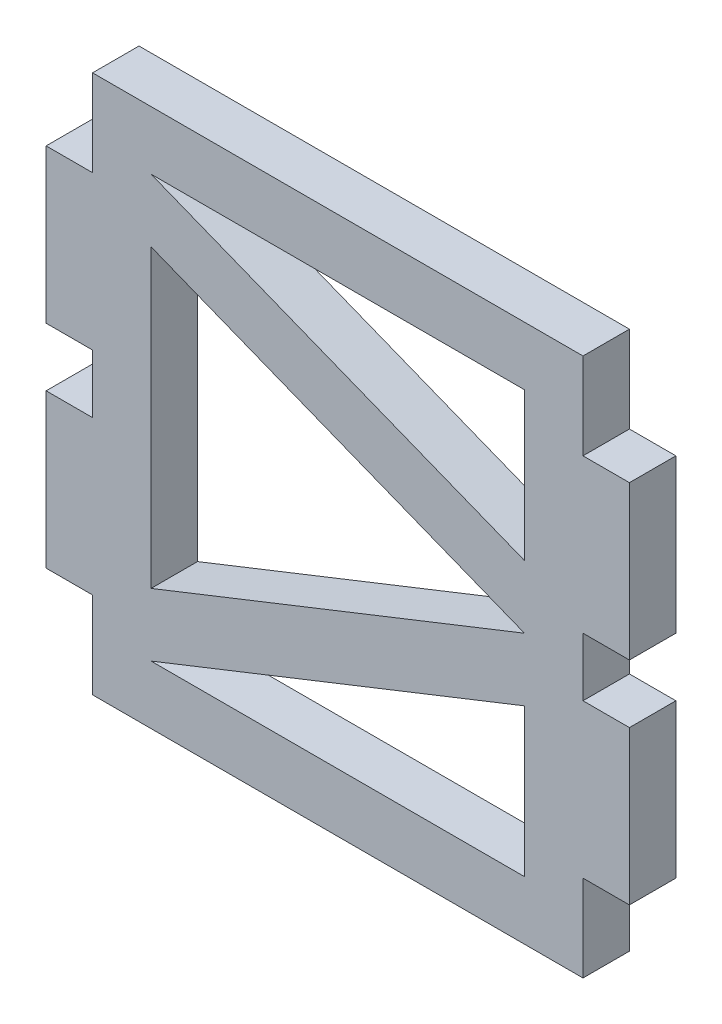
SolidWorks part; units mm, degrees
material "Mahogany"
ref_plane "Front Plane" through (0, 0, 0) normal (0, 0, 1) x (1, 0, 0)
ref_plane "Top Plane" through (0, 0, 0) normal (0, 1, 0) x (1, 0, 0)
ref_plane "Right Plane" through (0, 0, 0) normal (1, 0, 0) x (0, 0, -1)
sketch "Sketch1" plane through (0, 0, 0) normal (0, 0, 1) x (1, 0, 0)
  line L0 (3.175, 27.5) -> (0, 27.5) construction
  line L1 (0, 27.5) -> (0, 38) construction
  line L2 (3.175, 38) -> (0, 38) construction
  line L3 (3.175, 42) -> (0, 42) construction
  line L4 (0, 42) -> (0, 52.5) construction
  line L5 (3.175, 52.5) -> (0, 52.5) construction
  line L6 (36.7, 27.5) -> (39.875, 27.5) construction
  line L7 (39.875, 27.5) -> (39.875, 38) construction
  line L8 (36.7, 38) -> (39.875, 38) construction
  line L9 (36.7, 42) -> (39.875, 42) construction
  line L10 (39.875, 42) -> (39.875, 52.5) construction
  line L11 (36.7, 52.5) -> (39.875, 52.5) construction
  line L12 (3.175, 27.5) -> (0, 27.5)
  line L13 (0, 27.5) -> (0, 38)
  line L14 (3.175, 38) -> (0, 38)
  line L15 (3.175, 42) -> (0, 42)
  line L16 (0, 42) -> (0, 52.5)
  line L17 (3.175, 52.5) -> (0, 52.5)
  line L18 (36.7, 27.5) -> (39.875, 27.5)
  line L19 (39.875, 27.5) -> (39.875, 38)
  line L20 (36.7, 38) -> (39.875, 38)
  line L21 (36.7, 42) -> (39.875, 42)
  line L22 (39.875, 42) -> (39.875, 52.5)
  line L23 (36.7, 52.5) -> (39.875, 52.5)
  line L24 (39.875, 42) -> (39.875, 38) construction
  line L25 (0, 42) -> (0, 38) construction
  line L26 (0, 40) -> (39.875, 40) construction
  line L27 (36.7, 42) -> (36.7, 38)
  line L28 (3.175, 42) -> (3.175, 38)
  line L29 (36.7, 52.5) -> (36.7, 58.4125)
  line L30 (36.7, 58.4125) -> (3.175, 58.4125)
  line L31 (3.175, 58.4125) -> (3.175, 52.5)
  line L32 (36.7, 27.5) -> (36.7, 21.5875)
  line L33 (36.7, 21.5875) -> (3.175, 21.5875)
  line L34 (3.175, 21.5875) -> (3.175, 27.5)
  line L35 (32.7, 40) -> (7.175, 50.1102)
  line L36 (7.175, 50.1102) -> (7.175, 29.8898)
  line L37 (7.175, 29.8898) -> (32.7, 40)
  line L38 (32.7, 54.4125) -> (7.175, 54.4125)
  line L39 (7.175, 54.4125) -> (32.7, 44.3023)
  line L40 (32.7, 44.3023) -> (32.7, 54.4125)
  line L41 (32.7, 25.5875) -> (32.7, 35.6977)
  line L42 (32.7, 35.6977) -> (7.175, 25.5875)
  line L43 (7.175, 25.5875) -> (32.7, 25.5875)
  line L44 (3.175, 21.5875) -> (0, 21.5875) construction
  line L45 (0, 58.4125) -> (3.175, 58.4125) construction
  line L46 (3.175, 21.5875) -> (0, 21.5875) construction
  line L47 (0, 58.4125) -> (3.175, 58.4125) construction
  point P33 (0, 0)
  point P34 (0, 0)
  point P35 (30.168, 44.6091)
  point P36 (31.6013, 45.6263)
  point P37 (28.1336, 44.6091)
  point P38 (32.7, 40)
  point P39 (31.5088, 40)
  point P40 (7.175, 27.5)
  point P41 (3.175, 58.4125)
  point P42 (0, 0)
  point P43 (0, 0)
  dimension "D1" = 4
  dimension "D2" = 4
  dimension "D3" = 4
  dimension "D4" = 4
  dimension "D5" = 4
extrude "Boss-Extrude1" add sketch "Sketch1" along normal up to surface (3.175 mm away)
